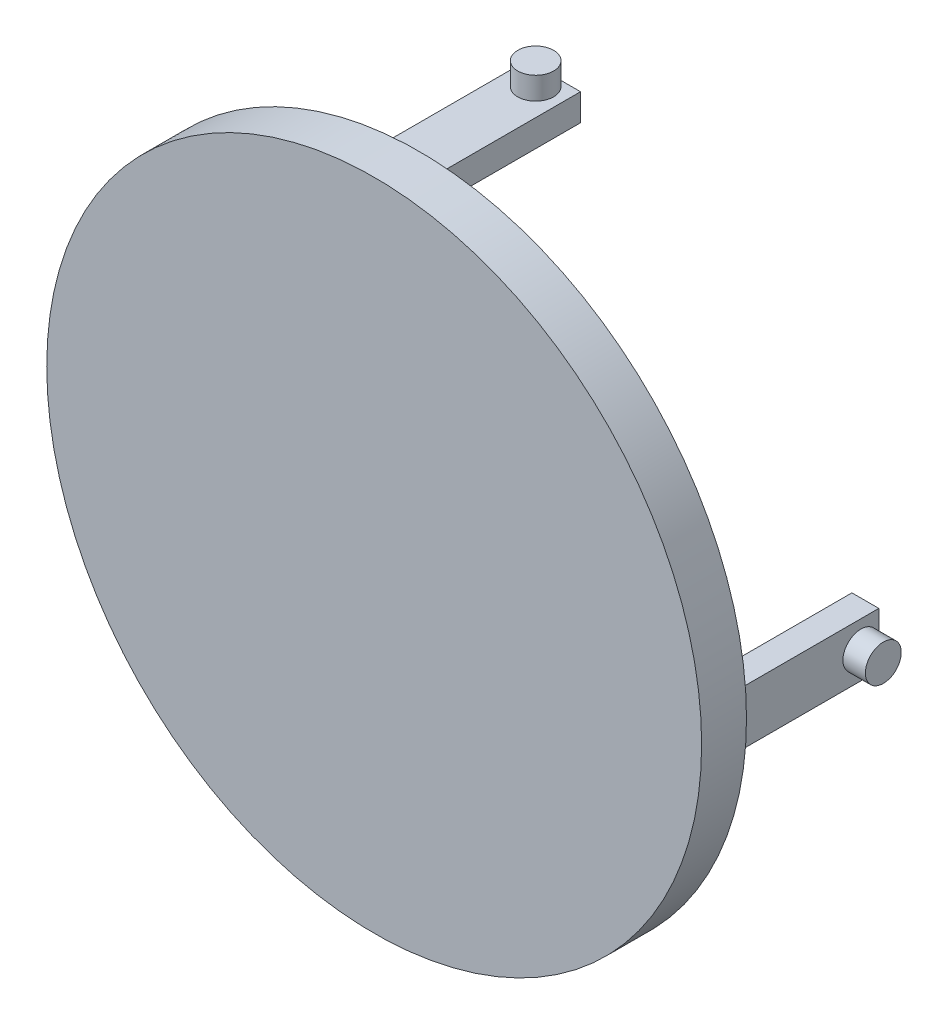
SolidWorks part; units mm, degrees
ref_plane "Front Plane" through (0, 0, 0) normal (0, 0, 1) x (1, 0, 0)
ref_plane "Top Plane" through (0, 0, 0) normal (0, 1, 0) x (1, 0, 0)
ref_plane "Right Plane" through (0, 0, 0) normal (1, 0, 0) x (0, 0, -1)
sketch "Sketch1" plane through (0, 0, 0) normal (0, 0, 1) x (1, 0, 0)
  circle A0 centre (0, 0) radius 36.5
  dimension "D1" = 73
extrude "Boss-Extrude1" add sketch "Sketch1" along normal blind 5
ref_plane "Plane1" through (0, 0, 0) normal (0, 0, -1) x (-1, 0, 0)
sketch "Sketch4" plane through (0, 0, 0) normal (0, 0, -1) x (-1, 0, 0)
  line L6 (-36.25, 3) -> (-33.25, 3)
  line L7 (-36.25, 3) -> (-36.25, -3)
  line L8 (-33.25, 3) -> (-33.25, -3)
  line L9 (-33.25, -3) -> (-36.25, -3)
  line L11 (36.25, 3) -> (36.25, -3)
  line L12 (-3, 36.25) -> (-3, 33.25)
  line L13 (3, 36.25) -> (-3, 36.25)
  line L14 (-3, 33.25) -> (3, 33.25)
  line L15 (3, 33.25) -> (3, 36.25)
  line L16 (36.25, -3) -> (33.25, -3)
  line L17 (3, -36.25) -> (-3, -36.25)
  line L18 (-3, -36.25) -> (-3, -33.25)
  line L19 (-3, -33.25) -> (3, -33.25)
  line L20 (3, -33.25) -> (3, -36.25)
  line L21 (33.25, -3) -> (33.25, 3)
  line L22 (33.25, 3) -> (36.25, 3)
  circle A5 centre (0, 0) radius 36.25 construction
  dimension "D1" = 72.5
extrude "Boss-Extrude4" add sketch "Sketch4" along normal blind 15
sketch "Sketch6" plane through (36.25, 0, 0) normal (1, 0, 0) x (0, 0, -1)
  circle A0 centre (13, 0) radius 2
extrude "Boss-Extrude6" add sketch "Sketch6" along normal blind 2.5
sketch "Sketch7" plane through (0, -36.25, -62.5) normal (0, 1, 0) x (1, 0, 0)
  line L0 (-3, -47.5) -> (3, -47.5) construction
  circle A0 centre (0, -49.5) radius 2
extrude "Boss-Extrude8" add sketch "Sketch7" against normal blind 2.5 contours A0
sketch "Sketch9" plane through (-36.25, 0, -62.5) normal (1, 0, 0) x (0, 0, -1)
  line L0 (-47.5, -3) -> (-47.5, 3) construction
  circle A0 centre (-49.5, 0) radius 2
extrude "Boss-Extrude9" add sketch "Sketch9" against normal blind 2.5
sketch "Sketch10" plane through (0, 36.25, 0) normal (0, -1, 0) x (-1, 0, 0)
  line L1 (3, 15) -> (-3, 15) construction
  circle A0 centre (0, 13) radius 2
extrude "Boss-Extrude10" add sketch "Sketch10" against normal blind 2.5
